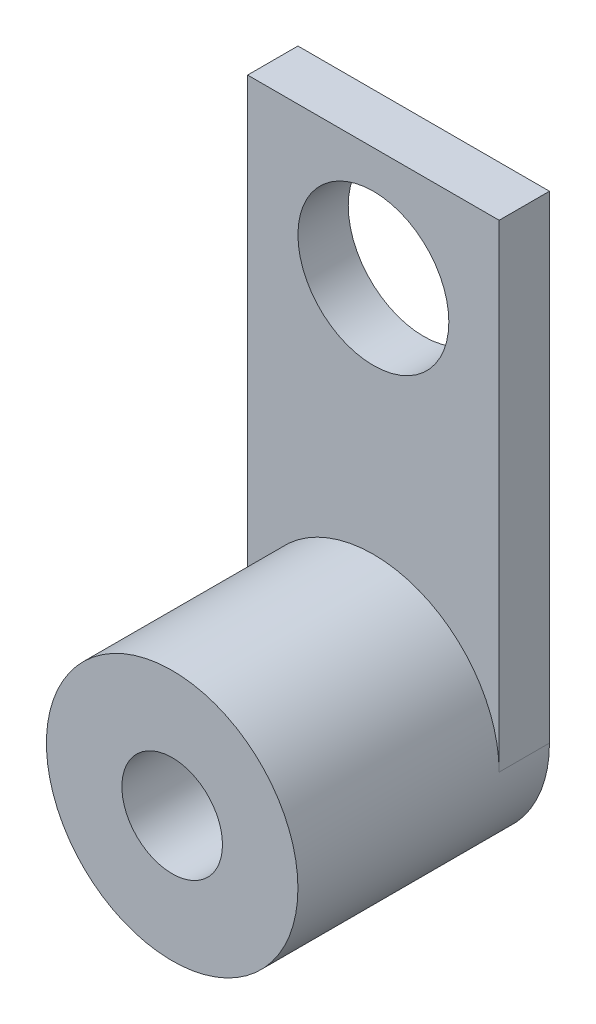
SolidWorks part; units mm, degrees
ref_plane "Front Plane" through (0, 0, 0) normal (1, 0, 0) x (0, 1, 0)
ref_plane "Top Plane" through (0, 0, 0) normal (0, 0, 1) x (0, 1, 0)
ref_plane "Right Plane" through (0, 0, 0) normal (0, 1, 0) x (-1, 0, 0)
sketch "Sketch3" plane through (0, 0, 0) normal (0, 0, 1) x (0, 1, 0)
  circle A0 centre (0, 0) radius 63.5
  circle A1 centre (0, 0) radius 25.4
  dimension "D1" = 127
  dimension "D2" = 50.8
extrude "Boss-Extrude1" add sketch "Sketch3" along normal blind 127
sketch "Sketch4" plane through (0, 0, 0) normal (0, 0, 1) x (0, 1, 0)
  line L1 (0, 63.5) -> (241.3, 63.5)
  line L2 (0, -63.5) -> (241.3, -63.5)
  line L3 (241.3, 63.5) -> (241.3, -63.5)
  line L4 (0, -69.85) -> (0, 69.85) construction
  line L5 (-69.85, 0) -> (69.85, 0) construction
  circle A0 centre (0, 0) radius 63.5 construction
  arc A1 (0, 63.5) -> (0, -63.5) centre (0, 0) ccw
  circle A2 centre (0, 0) radius 25.4 construction
  circle A3 centre (0, 0) radius 25.4
  circle A4 centre (184.15, 0) radius 38.1
  point P15 (63.5, 0)
  dimension "D2" = 76.2
  dimension "D1" = 177.8
  dimension "D3" = 57.15
extrude "Boss-Extrude2" add sketch "Sketch4" along normal blind 25.4
